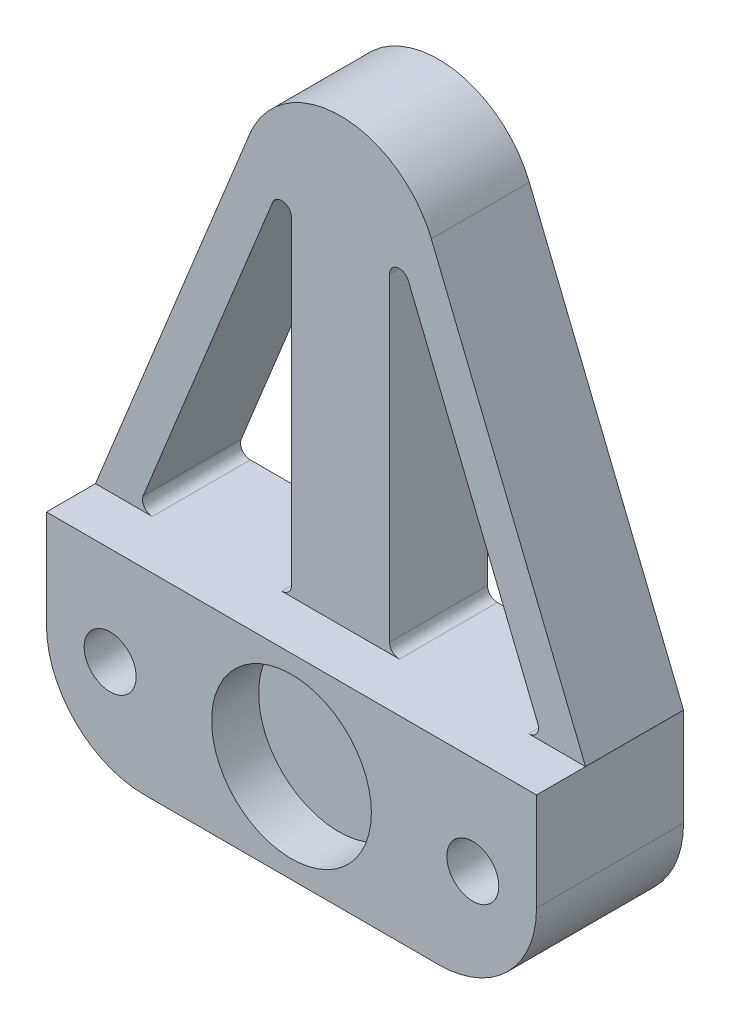
SolidWorks part; units mm, degrees
material "POM 乙缩醛共聚物"
ref_plane "前视基准面" through (0, 0, 0) normal (0, 0, 1) x (1, 0, 0)
ref_plane "上视基准面" through (0, 0, 0) normal (0, 1, 0) x (1, 0, 0)
ref_plane "右视基准面" through (0, 0, 0) normal (1, 0, 0) x (0, 0, -1)
sketch "草图1" plane through (0, 0, 0) normal (0, 0, 1) x (1, 0, 0)
  line L0 (-18.5, 0) -> (18.5, 0) construction
  line L1 (25, -10) -> (-25, -10)
  line L2 (25, -10) -> (25, 10)
  line L3 (25, 10) -> (-25, 10)
  line L4 (-25, -10) -> (-25, 10)
  line L5 (25, -10) -> (-25, 10) construction
  line L6 (25, 10) -> (-25, -10) construction
  circle A0 centre (-18.5, 0) radius 2.65
  circle A1 centre (18.5, 0) radius 2.65
  point P0 (0, 0)
  point P12 (0, 0)
  dimension "D3" = 5.3
  dimension "D1" = 20
  dimension "D2" = 50
  dimension "D4" = 37
extrude "凸台-拉伸1" add sketch "草图1" along normal blind 15
sketch "草图2" plane through (0, 0, 0) normal (0, 0, -1) x (-1, 0, 0)
  circle A0 centre (0, 0) radius 5.175
  dimension "D1" = 10.35
extrude "切除-拉伸1" cut sketch "草图2" against normal blind 5.5
sketch "草图3" plane through (0, 0, 15) normal (0, 0, 1) x (1, 0, 0)
  circle A0 centre (0, 0) radius 8.15
  dimension "D1" = 16.3
extrude "切除-拉伸2" cut sketch "草图3" against normal blind 4.8
sketch "草图4" plane through (0, 0, 0) normal (0, 0, -1) x (-1, 0, 0)
  line L0 (25, 10) -> (9.2657, 48.7612)
  line L1 (-9.2657, 48.7612) -> (-25, 10)
  line L2 (0, 0) -> (0, 45) construction
  line L3 (25, 10) -> (-25, 10)
  arc A0 (9.2657, 48.7612) -> (-9.2657, 48.7612) centre (0, 45) ccw
  dimension "D2" = 10
  dimension "D1" = 45
extrude "凸台-拉伸2" add sketch "草图4" against normal blind 10
sketch "草图5" plane through (0, 0, 0) normal (0, 0, -1) x (-1, 0, 0)
  circle A0 centre (0, 45) radius 8.2
  dimension "D1" = 16.4
extrude "切除-拉伸3" cut sketch "草图5" against normal blind 6
sketch "草图6" plane through (0, 0, 0) normal (0, 0, -1) x (-1, 0, 0)
  line L0 (-20.683, 10) -> (-5, 48.6349)
  line L1 (-5, 48.6349) -> (-5, 10)
  line L2 (-5, 10) -> (-20.683, 10)
  line L3 (0, 0) -> (0, 45) construction
  line L4 (-9.2657, 48.7612) -> (-25, 10) construction
  line L5 (5, 10) -> (20.683, 10)
  line L6 (5, 48.6349) -> (5, 10)
  line L7 (20.683, 10) -> (5, 48.6349)
  dimension "D1" = 4
  dimension "D2" = 10
extrude "切除-拉伸4" cut sketch "草图6" against normal through all
fillet "圆角1" radius 1 6 edges at (-5, 48.6349, 8) (-20.683, 10, 5) (-5, 10, 5) (5, 48.6349, 8) (5, 10, 5) (20.683, 10, 5)
fillet "圆角3" radius 10 2 edges at (-25, -10, 7.5) (25, -10, 7.5)
